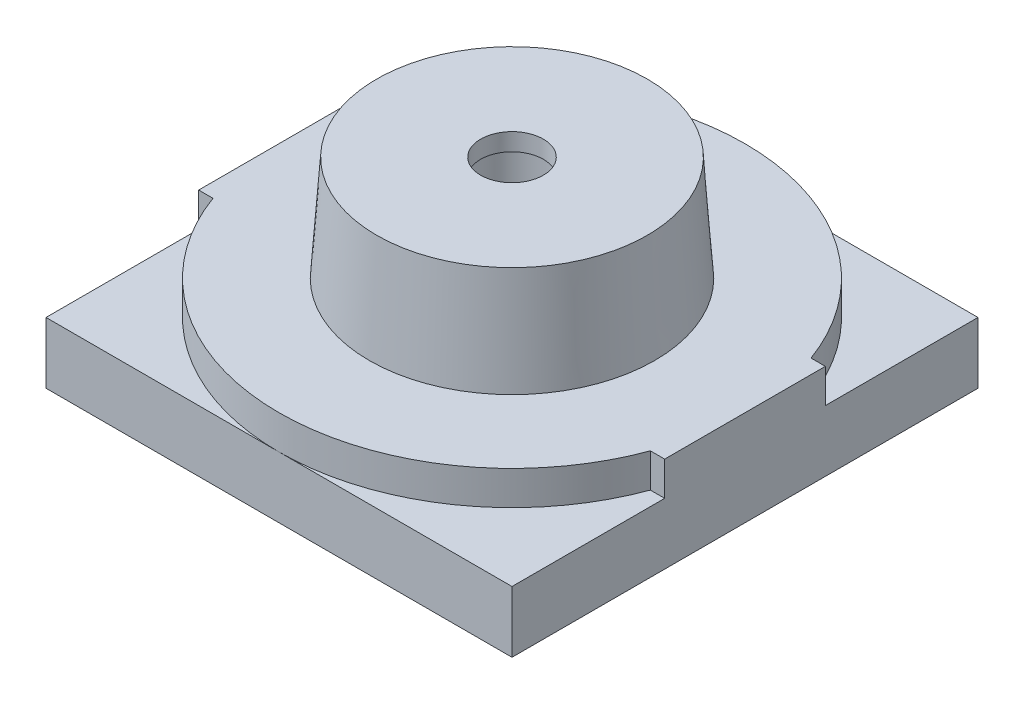
SolidWorks part; units mm, degrees
ref_plane "Front Plane" through (0, 0, 0) normal (0, 0, 1) x (1, 0, 0)
ref_plane "Top Plane" through (0, 0, 0) normal (0, 1, 0) x (1, 0, 0)
ref_plane "Right Plane" through (0, 0, 0) normal (1, 0, 0) x (0, 0, -1)
sketch "Sketch1" plane through (0, 0, 0) normal (0, 1, 0) x (1, 0, 0)
  line L1 (-3.505, -3.505) -> (3.505, -3.505)
  line L2 (-3.505, -3.505) -> (-3.505, 3.505)
  line L3 (-3.505, 3.505) -> (3.505, 3.505)
  line L4 (3.505, -3.505) -> (3.505, 3.505)
  line L5 (-3.505, -3.505) -> (3.505, 3.505) construction
  line L6 (-3.505, 3.505) -> (3.505, -3.505) construction
  point P0 (0, 0)
  dimension "D1" = 7.01
  dimension "D2" = 7.01
extrude "Boss-Extrude1" add sketch "Sketch1" along normal blind 0.92
sketch "Sketch2" plane through (0, 0.92, 0) normal (0, 1, 0) x (1, 0, 0)
  circle A0 centre (0, 0) radius 3.505
  dimension "D1" = 7.01
extrude "Boss-Extrude2" add sketch "Sketch2" along normal blind 0.83
sketch "Sketch3" plane through (0, 1.75, 0) normal (0, 1, 0) x (1, 0, 0)
  circle A0 centre (0, 0) radius 2.135
  dimension "D1" = 4.27
extrude "Boss-Extrude3" add sketch "Sketch3" along normal blind 1.7521
sketch "Sketch4" plane through (0, 0, 0) normal (0, -1, 0) x (1, 0, 0)
  circle A0 centre (0, 0) radius 2.085
extrude "Cut-Extrude1" cut sketch "Sketch4" against normal blind 1
sketch "Sketch5" plane through (0, 3.5021, 0) normal (0, 1, 0) x (1, 0, 0)
  line L1 (-1.325, -1.325) -> (1.325, -1.325)
  line L2 (-1.325, -1.325) -> (-1.325, 1.325)
  line L3 (-1.325, 1.325) -> (1.325, 1.325)
  line L4 (1.325, -1.325) -> (1.325, 1.325)
  line L5 (-1.325, -1.325) -> (1.325, 1.325) construction
  line L6 (-1.325, 1.325) -> (1.325, -1.325) construction
  point P0 (0, 0)
  dimension "D1" = 2.65
  dimension "D2" = 2.65
extrude "Cut-Extrude2" cut sketch "Sketch5" against normal through all both and the other way through all
sketch "Sketch6" plane through (0, 0, 0) normal (0, -1, 0) x (1, 0, 0)
  line L1 (3, 3) -> (-3, 3)
  line L2 (3, 3) -> (3, -3)
  line L3 (3, -3) -> (-3, -3)
  line L4 (-3, 3) -> (-3, -3)
  line L5 (4.371, 5.3581) -> (-4.4723, 5.3581)
  line L6 (4.371, 5.3581) -> (4.371, -5.3635)
  line L7 (4.371, -5.3635) -> (-4.4723, -5.3635)
  line L8 (-4.4723, 5.3581) -> (-4.4723, -5.3635)
  circle A0 centre (0, 0) radius 3
  line M11 (3.505, -3.505) -> (3.505, 3.505)
  line M12 (3.505, 3.505) -> (-3.505, 3.505)
  line M13 (-3.505, 3.505) -> (-3.505, -3.505)
  line M14 (-3.505, -3.505) -> (3.505, -3.505)
  dimension "D1" = 3
  dimension "D2" = 3
  dimension "D3" = 3
  dimension "D4" = 3
extrude "Cut-Extrude3" cut sketch "Sketch6" against normal blind 10 contours L5 L8 L7 L6 M11 M14 M13 M12 | L4 L1 L2 L3 M14 M11 M12 M13
sketch "Sketch7" plane through (0, 1.75, 0) normal (0, 1, 0) x (1, 0, 0)
  line L1 (-4.5391, -5.4068) -> (4.3161, -5.4068)
  line L2 (-4.5391, -5.4068) -> (-4.5391, 4.3224)
  line L3 (-4.5391, 4.3224) -> (4.3161, 4.3224)
  line L4 (4.3161, -5.4068) -> (4.3161, 4.3224)
  circle A0 centre (0, 0) radius 3
extrude "Cut-Extrude4" cut sketch "Sketch7" against normal up to surface (0.83 mm away) up to face at (-2.6282, 0.92, 2.6282)
sketch "Sketch8" plane through (0, 1, 0) normal (0, -1, 0) x (1, 0, 0)
  line L1 (1.3882, 1.4104) -> (-1.3829, 1.4104)
  line L2 (1.3882, 1.4104) -> (1.3882, -1.3633)
  line L3 (1.3882, -1.3633) -> (-1.3829, -1.3633)
  line L4 (-1.3829, 1.4104) -> (-1.3829, -1.3633)
extrude "Boss-Extrude4" add sketch "Sketch8" against normal up to surface (2.5021 mm away) up to face at (0, 3.5021, 0)
sketch "Sketch9" plane through (0, 3.5021, 0) normal (0, 1, 0) x (1, 0, 0)
  circle A0 centre (0, 0) radius 0.554
extrude "Cut-Extrude5" cut sketch "Sketch9" against normal blind 0.3
sketch "Sketch10" plane through (0, 3.2021, 0) normal (0, 1, 0) x (1, 0, 0)
  circle A0 centre (0, 0) radius 0.47
  dimension "D1" = 0.94
extrude "Cut-Extrude6" cut sketch "Sketch10" against normal blind 100
sketch "Sketch11" plane through (0, 1, 0) normal (0, -1, 0) x (1, 0, 0)
  circle A0 centre (0, 0) radius 1.501
extrude "Cut-Extrude7" cut sketch "Sketch11" against normal blind 0.48
sketch "Sketch12" plane through (0, 1.48, 0) normal (0, -1, 0) x (1, 0, 0)
  circle A0 centre (0, 0) radius 0.817
extrude "Cut-Extrude8" cut sketch "Sketch12" against normal blind 0.7
sketch "Sketch14" plane through (0, 2.18, 0) normal (0, -1, 0) x (1, 0, 0)
  circle A1 centre (0, 0) radius 0.582
extrude "Cut-Extrude9" cut sketch "Sketch14" against normal blind 0.56
sketch "Sketch15" plane through (0, 3.2021, 0) normal (0, 1, 0) x (1, 0, 0)
  circle A0 centre (0, 0) radius 0.47
  circle A1 centre (0, 0) radius 0.554
extrude "Boss-Extrude5" add sketch "Sketch15" along normal blind 0.05
sketch "Sketch16" plane through (0, 1, 0) normal (0, -1, 0) x (1, 0, 0)
  circle A0 centre (0, 0) radius 1.63
  circle A1 centre (0, 0) radius 2.085
extrude "Boss-Extrude6" add sketch "Sketch16" along normal blind 0.79
sketch "Sketch17" plane through (0, 1, 0) normal (0, -1, 0) x (1, 0, 0)
  circle A0 centre (0, 0) radius 1.501
  circle A1 centre (0, 0) radius 1.63
extrude "Boss-Extrude7" add sketch "Sketch17" along normal blind 0.53
sketch "Sketch18" plane through (0, 3.5021, 0) normal (0, 1, 0) x (1, 0, 0)
  circle A0 centre (0, 0) radius 1.5
  circle A1 centre (0, 0) radius 2.5725
extrude "Cut-Extrude10" cut sketch "Sketch18" against normal up to surface (1.7521 mm away) up to face at (0, 1.75, 2.135)
sketch "Sketch19" plane through (0, 0.21, 0) normal (0, -1, 0) x (1, 0, 0)
  circle A0 centre (0, 0) radius 1.705
  circle A1 centre (0, 0) radius 2.085
extrude "Boss-Extrude8" add sketch "Sketch19" along normal up to surface (0.21 mm away) up to face at (0, 0, -2.085)
sketch "Sketch20" plane through (0, 1.75, 0) normal (0, 1, 0) x (1, 0, 0)
  line L1 (3.4584, 7.4306) -> (-3.2486, 7.4306)
  line L2 (3.4584, 7.4306) -> (3.4584, -4.0115)
  line L3 (3.4584, -4.0115) -> (-3.2486, -4.0115)
  line L4 (-3.2486, 7.4306) -> (-3.2486, -4.0115)
  circle A0 centre (0, 0) radius 1.8
extrude "Cut-Extrude11" cut sketch "Sketch20" against normal up to surface (0.83 mm away) up to face at (-2.2071, 0.92, -2.2071)
sketch "Sketch21" plane through (0, 0.92, 0) normal (0, 1, 0) x (1, 0, 0)
  line L1 (1.9, 1.9) -> (-1.9, 1.9)
  line L2 (1.9, 1.9) -> (1.9, -1.9)
  line L3 (1.9, -1.9) -> (-1.9, -1.9)
  line L4 (-1.9, 1.9) -> (-1.9, -1.9)
  line L5 (3.0928, 8.1854) -> (-3.4275, 8.1854)
  line L6 (3.0928, 8.1854) -> (3.0928, -7.2732)
  line L7 (3.0928, -7.2732) -> (-3.4275, -7.2732)
  line L8 (-3.4275, 8.1854) -> (-3.4275, -7.2732)
  dimension "D1" = 1.9
  dimension "D2" = 1.9
  dimension "D3" = 1.9
  dimension "D4" = 1.9
extrude "Cut-Extrude12" cut sketch "Sketch21" against normal blind 10
sketch "Sketch23" plane through (0, 0, 0) normal (0, -1, 0) x (1, 0, 0)
  line L0 (1.9, -1.9) -> (1.9, 1.9) construction
  line L1 (3.495, 3.495) -> (-3.495, 3.495)
  line L2 (3.495, 3.495) -> (3.495, -3.495)
  line L3 (3.495, -3.495) -> (-3.495, -3.495)
  line L4 (-3.495, 3.495) -> (-3.495, -3.495)
  line L5 (1.9, 1.9) -> (-1.9, 1.9) construction
  line L7 (1.7188, 1.7355) -> (-1.7837, 1.7355)
  line L8 (1.7188, 1.7355) -> (1.7188, -1.8128)
  line L9 (1.7188, -1.8128) -> (-1.7837, -1.8128)
  line L10 (-1.7837, 1.7355) -> (-1.7837, -1.8128)
  dimension "D1" = 6.99
  dimension "D2" = 6.99
  dimension "D3" = 1.595
  dimension "D4" = 1.595
extrude "Boss-Extrude9" add sketch "Sketch23" against normal up to surface (0.92 mm away) up to face at (0, 0.92, -1.8)
sketch "Sketch24" plane through (0, 3.5021, 0) normal (0, 1, 0) x (1, 0, 0)
  line L1 (-2.5462, -2.722) -> (3.5113, -2.722)
  line L2 (-2.5462, -2.722) -> (-2.5462, 2.619)
  line L3 (-2.5462, 2.619) -> (3.5113, 2.619)
  line L4 (3.5113, -2.722) -> (3.5113, 2.619)
extrude "Cut-Extrude14" cut sketch "Sketch24" against normal blind 0.13
sketch "Sketch25" plane through (0, 0.92, 0) normal (0, 1, 0) x (1, 0, 0)
  circle A0 centre (0, 0) radius 3.495
  circle A1 centre (0, 0) radius 1.6791
extrude "Boss-Extrude10" add sketch "Sketch25" along normal up to surface (0.83 mm away) up to face at (0, 1.75, 1.5)
sketch "Sketch26" plane through (0, 1.75, 0) normal (0, 1, 0) x (1, 0, 0)
  line L0 (3.495, 0) -> (3.495, 3.495) construction
  line L1 (2.695, -1.18) -> (3.495, -1.18)
  line L2 (2.695, -1.18) -> (2.695, 1.18)
  line L3 (2.695, 1.18) -> (3.495, 1.18)
  line L4 (3.495, -1.18) -> (3.495, 1.18)
  line L5 (0, -3.495) -> (3.495, -3.495) construction
  dimension "D1" = 0
  dimension "D2" = 2.36
  dimension "D3" = 0.8
  dimension "D4" = 2.315
extrude "Boss-Extrude11" add sketch "Sketch26" against normal up to surface (0.83 mm away) up to face at (2.5713, 0.92, 2.5713)
sketch "Sketch27" plane through (0, 1.75, 0) normal (0, 1, 0) x (1, 0, 0)
  line L0 (-3.495, -3.495) -> (0, -3.495) construction
  line L1 (-3.495, -1.18) -> (-2.6926, -1.18)
  line L2 (-3.495, -1.18) -> (-3.495, 1.18)
  line L3 (-3.495, 1.18) -> (-2.6926, 1.18)
  line L4 (-2.6926, -1.18) -> (-2.6926, 1.18)
  line L5 (-3.495, 3.495) -> (-3.495, 0) construction
  dimension "D1" = 2.315
  dimension "D2" = 2.36
  dimension "D3" = 0
extrude "Boss-Extrude12" add sketch "Sketch27" against normal up to surface (0.83 mm away) up to face at (-2.5713, 0.92, 2.5713)
sketch "Sketch28" plane through (0, 3.3721, 0) normal (0, 1, 0) x (1, 0, 0)
  circle A0 centre (0, 0) radius 2.14
  circle A1 centre (0, 0) radius 1.326
extrude "Boss-Extrude13" add sketch "Sketch28" against normal up to surface (1.6221 mm away) up to face at (0, 1.75, 0)
sketch "Sketch29" plane through (0, 0, 0) normal (0, -1, 0) x (1, 0, 0)
  circle A0 centre (0, 0) radius 2.5
extrude "Cut-Extrude15" cut sketch "Sketch29" against normal up to surface (0.21 mm away) up to face at (0, 0.21, -1.63)
sketch "Sketch30" plane through (-3.495, 0, 0) normal (-1, 0, 0) x (0, 0, 1)
  line L0 (-1.18, 1.75) -> (-3.495, 1.75) construction
  line L1 (-1.18, 0.92) -> (-1.205, 0.92)
  line L2 (-1.18, 0.92) -> (-1.18, 1.75)
  line L3 (-1.18, 1.75) -> (-1.205, 1.75)
  line L4 (-1.205, 0.92) -> (-1.205, 1.75)
  line L6 (1.18, 0.92) -> (3.495, 0.92) construction
  line L7 (1.18, 1.75) -> (1.205, 1.75)
  line L8 (1.18, 1.75) -> (1.18, 0.92)
  line L9 (1.18, 0.92) -> (1.205, 0.92)
  line L10 (1.205, 1.75) -> (1.205, 0.92)
  dimension "D1" = 0.025
  dimension "D2" = 0.025
extrude "Boss-Extrude14" add sketch "Sketch30" against normal blind 0.4
sketch "Sketch31" plane through (3.495, 0, 0) normal (1, 0, 0) x (0, 0, -1)
  line L0 (-3.495, 0.92) -> (-1.18, 0.92) construction
  line L1 (-1.18, 1.75) -> (-1.205, 1.75)
  line L2 (-1.18, 1.75) -> (-1.18, 0.92)
  line L3 (-1.18, 0.92) -> (-1.205, 0.92)
  line L4 (-1.205, 1.75) -> (-1.205, 0.92)
  line L5 (3.495, 0.92) -> (1.18, 0.92) construction
  line L6 (1.18, 1.75) -> (1.205, 1.75)
  line L7 (1.18, 1.75) -> (1.18, 0.92)
  line L8 (1.18, 0.92) -> (1.205, 0.92)
  line L9 (1.205, 1.75) -> (1.205, 0.92)
  dimension "D1" = 0.025
  dimension "D2" = 0.025
extrude "Boss-Extrude15" add sketch "Sketch31" against normal blind 0.4
sketch "Sketch32" plane through (0, 1.75, 0) normal (0, 1, 0) x (1, 0, 0)
  circle A0 centre (0, 0) radius 2.14
  circle A1 centre (0, 0) radius 5.1194
extrude "Cut-Extrude16" cut sketch "Sketch32" against normal blind 0.32
sketch "Sketch33" plane through (0, 3.3721, 0) normal (0, 1, 0) x (1, 0, 0)
  line L1 (-3.0793, 2.3809) -> (3.5054, 2.3809)
  line L2 (-3.0793, 2.3809) -> (-3.0793, -2.416)
  line L3 (-3.0793, -2.416) -> (3.5054, -2.416)
  line L4 (3.5054, 2.3809) -> (3.5054, -2.416)
extrude "Cut-Extrude17" cut sketch "Sketch33" against normal blind 0.37
sketch "Sketch35" plane through (0, 1.43, 0) normal (0, 1, 0) x (1, 0, 0)
  line L1 (-2.5741, 2.4336) -> (2.6093, 2.4336)
  line L2 (-2.5741, 2.4336) -> (-2.5741, -2.5961)
  line L3 (-2.5741, -2.5961) -> (2.6093, -2.5961)
  line L4 (2.6093, 2.4336) -> (2.6093, -2.5961)
  circle A0 centre (0, 0) radius 2.14
extrude "Cut-Extrude18" cut sketch "Sketch35" along normal up to surface (1.5721 mm away) draft 4
